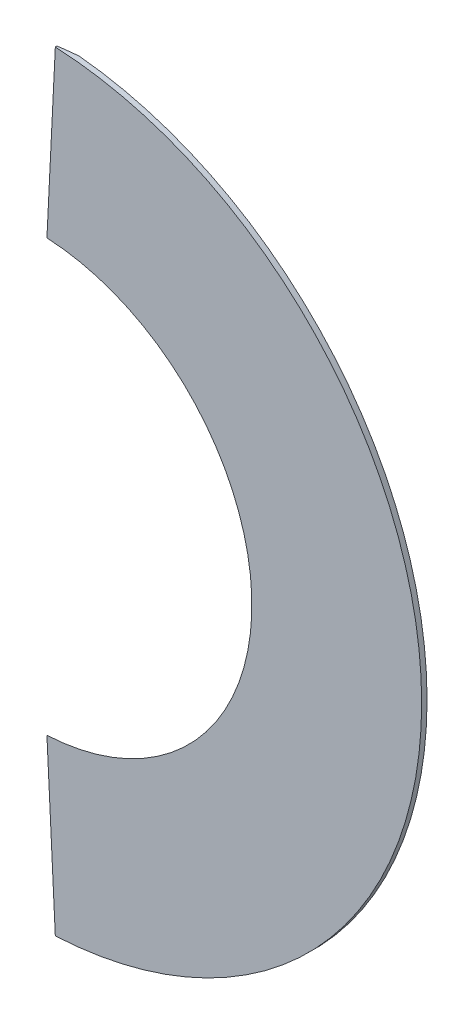
SolidWorks part; units mm, degrees
material "1023 Carbon Steel Sheet (SS)"
ref_plane "Front Plane" through (0, 0, 0) normal (0, 0, 1) x (1, 0, 0)
ref_plane "Top Plane" through (0, 0, 0) normal (0, 1, 0) x (1, 0, 0)
ref_plane "Right Plane" through (0, 0, 0) normal (1, 0, 0) x (0, 0, -1)
sketch "Sketch1" plane through (0, 0, 0) normal (0, 0, 1) x (1, 0, 0)
  line L0 (0, 0) -> (7.0646, 142.8254)
  line L1 (0, 0) -> (7.0651, -142.8254)
  arc A0 (7.0651, -142.8254) -> (7.0646, 142.8254) centre (0, 0) ccw
  dimension "D1" = 286
extrude "Boss-Extrude1" add sketch "Sketch1" along normal blind 2
sketch "Sketch2" plane through (0, 0, 0) normal (0, 0, -1) x (-1, 0, 0)
  circle A0 centre (0, 0) radius 80
  dimension "D1" = 160
extrude "Cut-Extrude1" cut sketch "Sketch2" against normal through all both and the other way through all
sketch "Sketch3" plane through (0, 0, 0) normal (0, 1, 0) x (1, 0, 0)
  line L0 (3.9522, -2) -> (13.9522, 0)
  line L1 (7.0646, 0) -> (3.9522, 0) construction
  line L2 (13.9522, 0) -> (3.9522, 0)
  line L3 (3.9522, 0) -> (3.9522, -2)
  dimension "D1" = 10
extrude "Cut-Extrude2" cut sketch "Sketch3" against normal through all both and the other way through all
sketch "Sketch4" plane through (0, 0, 0) normal (0, 1, 0) x (1, 0, 0)
  line L0 (0, 0) -> (0, 39.5574) construction
sketch "Sketch5" plane through (0, 0, 0) normal (0, 1, 0) x (1, 0, 0)
  line L0 (0, -2) -> (80, -2) construction
  line L1 (80, -2) -> (90, 0)
  line L3 (143, 0) -> (13.9522, 0) construction
  line L6 (80, -2) -> (80, 0)
  line L7 (80, 0) -> (13.9522, 0) construction
  line L8 (80, 0) -> (90, 0)
revolve "Cut-Revolve1" cut sketch "Sketch5" angle 360 about L0
